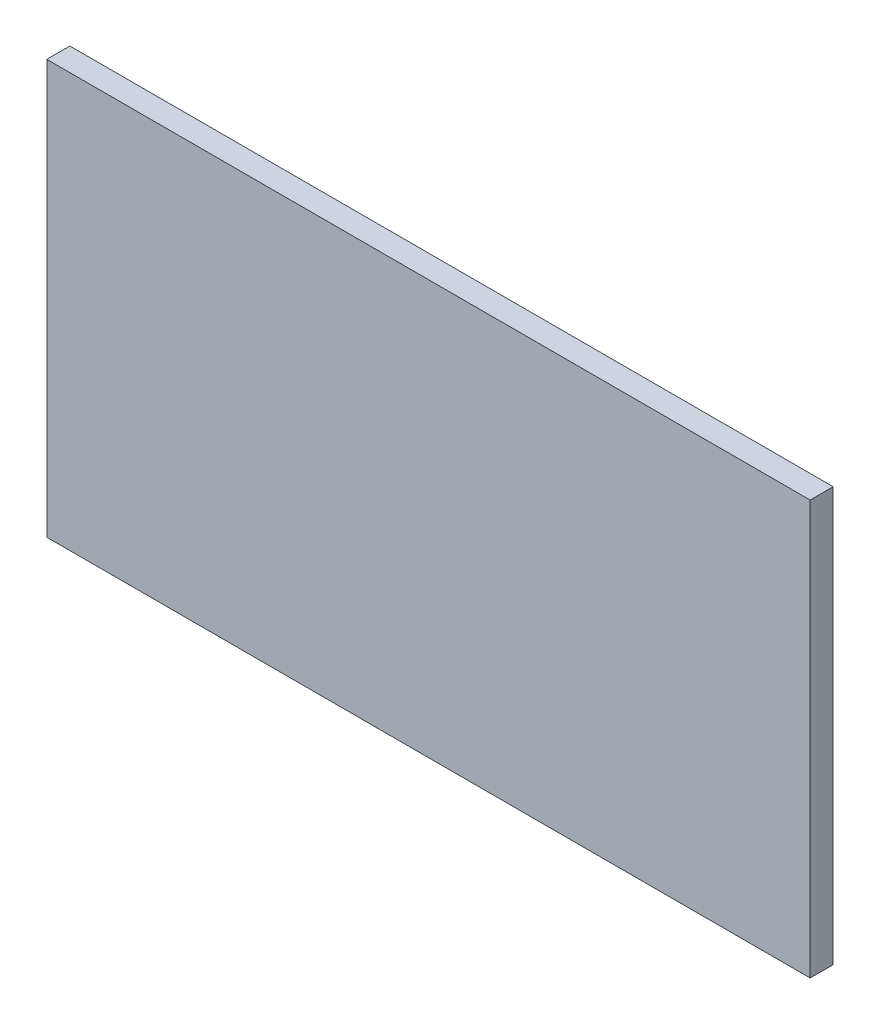
SolidWorks part; units mm, degrees
ref_plane "Front Plane" through (0, 0, 0) normal (0, 0, 1) x (1, 0, 0)
ref_plane "Top Plane" through (0, 0, 0) normal (0, 1, 0) x (1, 0, 0)
ref_plane "Right Plane" through (0, 0, 0) normal (1, 0, 0) x (0, 0, -1)
sketch "Sketch1" plane through (0, 0, 0) normal (0, 0, 1) x (1, 0, 0)
  line L0 (-16.0635, 8.5635) -> (17.0635, 8.5635)
  line L1 (17.0635, 8.5635) -> (17.0635, -9.4)
  line L2 (17.0635, -9.4) -> (-16.0635, -9.4)
  line L3 (-16.0635, -9.4) -> (-16.0635, 8.5635)
extrude "Component_Outline" add sketch "Sketch1" along normal blind 1 separate body
sketch3d "3DSketch1"
  line L0 (0, 0, 0) -> (1, 0, 0)
  line L1 (0, 0, 0) -> (0, 1, 0)
  line L2 (0, 0, 0) -> (0, 0, 1)
  point P0 (0, 0, 0)
